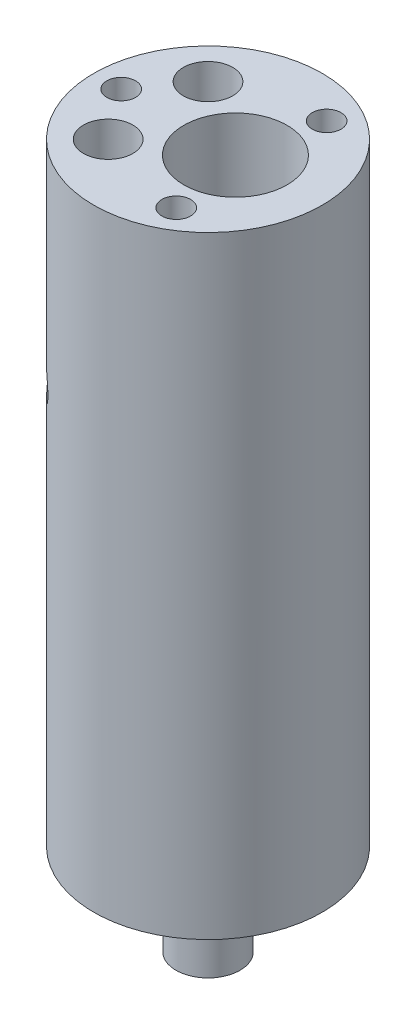
SolidWorks part; units mm, degrees
material "Polyetheretherketone (PEEK)"
ref_plane "Front Plane" through (0, 0, 0) normal (0, 0, 1) x (1, 0, 0)
ref_plane "Top Plane" through (0, 0, 0) normal (0, 1, 0) x (1, 0, 0)
ref_plane "Right Plane" through (0, 0, 0) normal (1, 0, 0) x (0, 0, -1)
sketch "Sketch1" plane through (0, 0, 0) normal (0, 1, 0) x (1, 0, 0)
  line L0 (0, 0) -> (0, 65.9412) construction
  line L1 (-0.1999, 0) -> (76.5452, 0) construction
  line L2 (0, 0) -> (-62.2942, 62.2942) construction
  line L3 (0, 0) -> (69.8455, 69.8455) construction
  circle A0 centre (0, 0) radius 12.75 construction
  circle A1 centre (0, 0) radius 7.5 construction
  circle A2 centre (0, 0) radius 12.5
  circle A3 centre (3, 0) radius 5.65
  circle A4 centre (0, 0) radius 2 construction
  dimension "D3" = 25.5
  dimension "D4" = 15
  dimension "D5" = 25
  dimension "D6" = 11.3
  dimension "D7" = 3
  dimension "D9" = 4
  dimension "D1" = 45
  dimension "D2" = 45
  dimension "D8" = 0
extrude "Boss-Extrude1" add sketch "Sketch1" along normal blind 60
sketch "Sketch2" plane through (0, 0, 0) normal (0, 0, 1) x (1, 0, 0)
  line L0 (0, 62.7965) -> (0, -1.233) construction
  line L1 (0, 0) -> (45.2674, 0) construction
  line L2 (-46.1392, 30) -> (57.3454, 30) construction
  line L3 (2, 30) -> (2, 72.519) construction
  line L4 (-17.5169, 60) -> (26.1432, 60) construction
  line L5 (-3.65, 30) -> (-3.65, 71.9777) construction
  point P12 (-3.65, 30)
  dimension "D1" = 30
  dimension "D2" = 2
  dimension "D3" = 60
  dimension "D4" = 5.65
sketch "Sketch3" plane through (0, 60, 0) normal (0, 1, 0) x (1, 0, 0)
  line L0 (0, 0) -> (0, 22.2598) construction
  line L1 (0, 0) -> (-19.9038, 19.9038) construction
  line L2 (0, 0) -> (-35355.3391, -35355.3391) construction
  line L3 (-200000, 0) -> (200045.2674, 0) construction
  line L4 (0.0503, 0.0872) -> (8.9973, 15.5838) construction
  line L5 (-0.4262, 0.7383) -> (9.0122, -15.6095) construction
  circle A0 centre (-5.4626, 5.4626) radius 4.65 construction
  circle A1 centre (-5.4626, -5.4626) radius 4.65 construction
  point P2 (-9.5, 0)
  point P14 (-5.4626, 5.4626)
  point P15 (-5.4626, -5.4626)
  point P19 (4.75, 8.2272)
  point P21 (4.75, -8.2272)
  dimension "D1" = 9.3
  dimension "D3" = 9.3
  dimension "D5" = 9.5
  dimension "D6" = 120
  dimension "D2" = 45
  dimension "D4" = 45
  dimension "D7" = 120
  dimension "D8" = 9.5
hole_wizard "Ø6.0mm Dowel Hole1" positions "Sketch5" profile "Sketch4" hole size "Ø6.0" standard "ANSI Metric"
sketch "Sketch5" plane through (0, 60, 0) normal (0, 1, 0) x (1, 0, 0)
  point P0 (-5.4626, 5.4626)
  point P3 (-5.4626, -5.4626)
sketch "Sketch4" plane through (-5.4626, 60, -5.4626) normal (1, 0, 0) x (0, 0, 1)
  line L0 (0, 0) -> (0, 10)
  line L1 (0, 10) -> (2.7, 10)
  line L2 (2.7, 10) -> (2.7, 0)
  line L5 (2.7, 0) -> (0, 0)
  line L10 (0, 10) -> (-2.7, 10) construction
  line L11 (0, -6.35) -> (0, 107.95) construction
  dimension "Hole Dia." = 5.4
  dimension "Hole Depth" = 10
  dimension "Drill Angle" = 180
ref_plane "Plane1" through (0, 0, 0) normal (0.7071, 0, -0.7071) x (-0.7071, 0, -0.7071)
sketch "Sketch10" plane through (0, 0, 0) normal (0.7071, 0, -0.7071) x (-0.7071, 0, -0.7071)
  line L0 (-21.1682, 30) -> (28.1057, 30) construction
  line L2 (32.6253, 30) -> (-40.5493, 30) construction
  point P4 (2.5809, 30)
sketch3d "3DSketch4"
  line L0 (14.9682, 30, 14.9682) -> (-19.8737, 30, -19.8737) construction
  line L1 (-15.7961, 30, 0) -> (14.4395, 30, 30.2356) construction
  line L2 (-46.1392, 30, 0) -> (57.3454, 30, 0) construction
  line L3 (0, 24.8692, 0) -> (-8.8754, 37.4209, -8.8754)
  line L4 (0, 62.7965, 0) -> (0, -1.233, 0) construction
  dimension "D1" = 45
hole_wizard "Tap Drill for M3 Helicoil1" positions "Sketch16" profile "Sketch15" hole size "M3x0.5" standard "ANSI Metric"
sketch "Sketch16" plane through (0, 60, 0) normal (0, 1, 0) x (1, 0, 0)
  point P0 (4.75, 8.2272)
  point P3 (4.75, -8.2272)
  point P6 (-9.5, 0)
sketch "Sketch15" plane through (4.75, 60, -8.2272) normal (1, 0, 0) x (0, 0, 1)
  line L0 (0, 0) -> (0, 10)
  line L1 (0, 10) -> (1.575, 10)
  line L2 (1.575, 10) -> (1.575, 0)
  line L5 (1.575, 0) -> (0, 0)
  line L10 (0, 10) -> (-1.575, 10) construction
  line L11 (0, -6.35) -> (0, 107.95) construction
  dimension "Hole Dia." = 3.15
  dimension "Hole Depth" = 10
  dimension "Drill Angle" = 180
sketch "Sketch17" plane through (0, 0, 0) normal (0, -1, 0) x (1, 0, 0)
  circle A0 centre (0, 0) radius 12.5
  dimension "D1" = 25
extrude "Boss-Extrude2" add sketch "Sketch17" along normal blind 7
sketch "Sketch18" plane through (0, -7, 0) normal (0, -1, 0) x (1, 0, 0)
  circle A0 centre (0, 0) radius 3.5
  dimension "D1" = 7
extrude "Boss-Extrude3" add sketch "Sketch18" along normal blind 10
sketch "Sketch19" plane through (0, -17, 0) normal (0, -1, 0) x (1, 0, 0)
  point P0 (0, 0)
hole_wizard "Ø3.0mm Dowel Hole1" positions "Sketch21" profile "Sketch20" hole size "Ø3.0" standard "ANSI Metric"
sketch "Sketch21" plane through (0, -7, 0) normal (0, -1, 0) x (-1, 0, 0)
  point P0 (0, 0)
sketch "Sketch20" plane through (0, -7, 0) normal (1, 0, 0) x (0, 0, 1)
  line L0 (0, 0) -> (0, 10)
  line L1 (0, 10) -> (1.65, 10)
  line L2 (1.65, 10) -> (1.65, 0)
  line L5 (1.65, 0) -> (0, 0)
  line L10 (0, 10) -> (-1.65, 10) construction
  line L11 (0, -6.35) -> (0, 107.95) construction
  dimension "Hole Dia." = 3.3
  dimension "Hole Depth" = 10
  dimension "Drill Angle" = 180
hole_wizard "Ø3.0mm Dowel Hole2" positions "Sketch23" profile "Sketch22" hole size "Ø3.0" standard "ANSI Metric" end condition up to next
sketch "Sketch23" plane through (0, 0, 0) normal (0, 1, 0) x (1, 0, 0)
  point P0 (0, 0)
sketch "Sketch22" plane through (0, 0, 0) normal (1, 0, 0) x (0, 0, 1)
  line L0 (0, 0) -> (0, 7)
  line L1 (0, 7) -> (1.65, 7)
  line L2 (1.65, 7) -> (1.65, 0)
  line L5 (1.65, 0) -> (0, 0)
  line L11 (0, -6.35) -> (0, 107.95) construction
  dimension "Thru Hole Dia." = 3.3
  dimension "Thru Hole Depth" = 7
ref_plane "Plane5" through (-8.8388, 0, -8.8388) normal (-0.7071, 0, -0.7071) x (-0.7071, 0, 0.7071)
sketch "Sketch24" plane through (-8.8388, 0, -8.8388) normal (-0.7071, 0, -0.7071) x (-0.7071, 0, 0.7071)
  circle A0 centre (0, 36.8821) radius 1.65
  dimension "D1" = 3.3
  dimension "D2" = 23.1179
sweep "Cut-Sweep5" cut profiles "Sketch24" path "3DSketch4"
ref_plane "Plane6" through (0, 0, 0) normal (-0.7071, 0, -0.7071) x (-0.7071, 0, 0.7071)
sketch3d "3DSketch7"
  line L0 (-3.6233, 30, 3.6233) -> (-12.5261, 42.5905, 12.5261)
  line L1 (-3.6233, 30, 3.6233) -> (-52.0539, 30, 52.0539) construction
  line L2 (-3.6233, 30, 3.6233) -> (0, 24.8759, 0)
  line L3 (0, 62.7965, 0) -> (0, -1.233, 0) construction
  line L5 (0, 60, 0) -> (-35355.3391, 60, 35355.3391) construction
  point P7 (-9.1531, 37.3732, 8.5129)
  dimension "D1" = 30
  dimension "D2" = 45
ref_plane "Plane7" through (-8.8388, 0, 8.8388) normal (-0.7071, 0, 0.7071) x (0.7071, 0, 0.7071)
sketch "Sketch27" plane through (-8.8388, 0, 8.8388) normal (-0.7071, 0, 0.7071) x (0.7071, 0, 0.7071)
  circle A0 centre (0, 36.9897) radius 1.65
  dimension "D1" = 3.3
sweep "Cut-Sweep6" cut profiles "Sketch27" path "3DSketch7"
sketch "Sketch31" plane through (0, 50, 0) normal (0, 1, 0) x (1, 0, 0)
  point P0 (-5.4626, 5.4626)
hole_wizard "Ø6.0mm Dowel Hole2" positions "Sketch33" profile "Sketch32" hole size "Ø6.0" standard "ANSI Metric"
sketch "Sketch33" plane through (0, 50, 0) normal (0, 1, 0) x (1, 0, 0)
  point P0 (-5.4626, 5.4626)
sketch "Sketch32" plane through (-5.4626, 50, -5.4626) normal (1, 0, 0) x (0, 0, 1)
  line L0 (0, 0) -> (0, 16.2427)
  line L1 (0, 16.2427) -> (1.65, 16.2427)
  line L2 (1.65, 16.2427) -> (1.65, 0)
  line L5 (1.65, 0) -> (0, 0)
  line L11 (0, -6.35) -> (0, 107.95) construction
  dimension "Thru Hole Dia." = 3.3
  dimension "Thru Hole Depth" = 16.2427
sketch "Sketch34" plane through (0, 50, 0) normal (0, 1, 0) x (1, 0, 0)
  point P0 (-5.4626, -5.4626)
hole_wizard "Ø6.0mm Dowel Hole3" positions "Sketch36" profile "Sketch35" hole size "Ø6.0" standard "ANSI Metric"
sketch "Sketch36" plane through (0, 50, 0) normal (0, 1, 0) x (1, 0, 0)
  point P0 (-5.4626, -5.4626)
sketch "Sketch35" plane through (-5.4626, 50, 5.4626) normal (1, 0, 0) x (0, 0, 1)
  line L0 (0, 0) -> (0, 16.1351)
  line L1 (0, 16.1351) -> (1.65, 16.1351)
  line L2 (1.65, 16.1351) -> (1.65, 0)
  line L5 (1.65, 0) -> (0, 0)
  line L11 (0, -6.35) -> (0, 107.95) construction
  dimension "Thru Hole Dia." = 3.3
  dimension "Thru Hole Depth" = 16.1351
sketch "Sketch37" plane through (0, -7, 0) normal (0, -1, 0) x (1, 0, 0)
  line L0 (-200017.5169, 0) -> (200026.1432, 0) construction
  line L1 (-100000.4262, -173205.819) -> (100009.0122, 173220.6903) construction
  line L2 (-99999.9497, 173204.9936) -> (100008.9973, -173220.6645) construction
  circle A0 centre (-9, 0) radius 3 construction
  point P0 (-9, 0)
  point P1 (4.5, 7.7942)
  point P5 (4.5, -7.7942)
  dimension "D4" = 6
  dimension "D1" = 9
  dimension "D2" = 9
  dimension "D3" = 9
hole_wizard "Ø6.0mm Dowel Hole4" positions "Sketch39" profile "Sketch40" hole size "Ø6.0" standard "ANSI Metric"
sketch "Sketch39" plane through (0, -7, 0) normal (0, -1, 0) x (-1, 0, 0)
  point P0 (-4.5, -7.7942)
  point P4 (9, 0)
  point P7 (-4.5, 7.7942)
sketch "Sketch40" plane through (4.5, -7, 7.7942) normal (1, 0, 0) x (0, 0, -1)
  line L0 (0, 0) -> (0, 10)
  line L1 (0, 10) -> (1.5, 10)
  line L2 (1.5, 10) -> (1.5, 0)
  line L5 (1.5, 0) -> (0, 0)
  line L10 (0, 10) -> (-1.5, 10) construction
  line L11 (0, -6.35) -> (0, 107.95) construction
  dimension "Hole Dia." = 3
  dimension "Hole Depth" = 10
  dimension "Drill Angle" = 180
